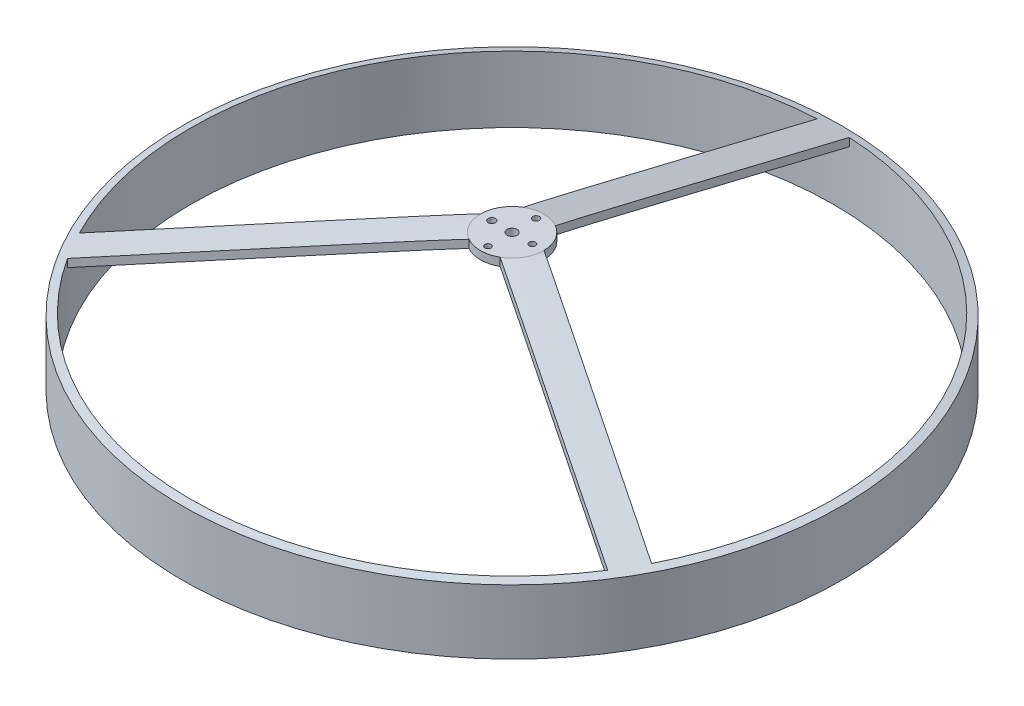
SolidWorks part; units mm, degrees
ref_plane "Front Plane" through (0, 0, 0) normal (0, 0, 1) x (1, 0, 0)
ref_plane "Top Plane" through (0, 0, 0) normal (0, 1, 0) x (1, 0, 0)
ref_plane "Right Plane" through (0, 0, 0) normal (1, 0, 0) x (0, 0, -1)
sketch "Sketch1" plane through (0, 0, 0) normal (0, 0, 1) x (1, 0, 0)
  line L0 (0, 50.8) -> (0, 53.975)
  line L1 (0, 53.975) -> (12.5, 53.975)
  line L2 (12.5, 53.975) -> (130.175, 25.4)
  line L3 (130.175, 25.4) -> (130.175, 0)
  line L4 (130.175, 0) -> (127, 0)
  line L5 (0, 50.8) -> (12.5, 50.8)
  line L6 (12.5, 50.8) -> (127, 22.996)
  line L7 (127, 22.996) -> (127, 0)
  point P0 (0, 0)
  point P8 (0, 0)
  point P11 (0, 0)
  dimension "D1" = 12.5
  dimension "D2" = 25.4
  dimension "D3" = 28.575
  dimension "D4" = 130.175
  dimension "D5" = 3.175
  dimension "D6" = 3.175
revolve "Revolve1" add sketch "Sketch1" angle 360 about L0
sketch "Sketch2" plane through (0, 53.975, 0) normal (0, 1, 0) x (1, 0, 0)
  line L1 (-6.35, 10.767) -> (-6.35, 126.8412)
  line L3 (6.35, 126.8412) -> (6.35, 10.767)
  line L4 (0, 0) -> (0, 196.1282) construction
  line L5 (12.4995, 0.1158) -> (113.0227, -57.9213)
  line L6 (106.6727, -68.9198) -> (6.1495, -10.8827)
  line L7 (-6.1495, -10.8827) -> (-106.6727, -68.9198)
  line L8 (-113.0227, -57.9213) -> (-12.4995, 0.1158)
  circle A0 centre (0, 0) radius 12.5
  circle A1 centre (0, 0) radius 127
  point P20 (0, 0)
  point P24 (0, 0)
  dimension "D1" = 254
  dimension "D2" = 25
  dimension "D3" = 12.7
  dimension "D4" = 6.35
  dimension "D5" = 3
extrude "Cut-Extrude1" cut sketch "Sketch2" against normal through all
sketch "Sketch5" plane through (0, 50.8, 0) normal (0, -1, 0) x (1, 0, 0)
  line L0 (0, 9.5) -> (0, -9.5) construction
  line L1 (8, 0) -> (-8, 0) construction
  line L2 (-6.35, 126.8412) -> (-6.35, 10.767) construction
  circle A0 centre (0, 0) radius 2
  circle A1 centre (0, 9.5) radius 1.2151
  circle A2 centre (8, 0) radius 1.2503
  circle A3 centre (0, -9.5) radius 1.3223
  circle A4 centre (-8, 0) radius 1.4479
  dimension "D5" = 2.8958
  dimension "D6" = 4
  dimension "D1" = 9.5
  dimension "D2" = 9.5
  dimension "D3" = 8
  dimension "D4" = 8
extrude "Cut-Extrude3" cut sketch "Sketch5" against normal through all
